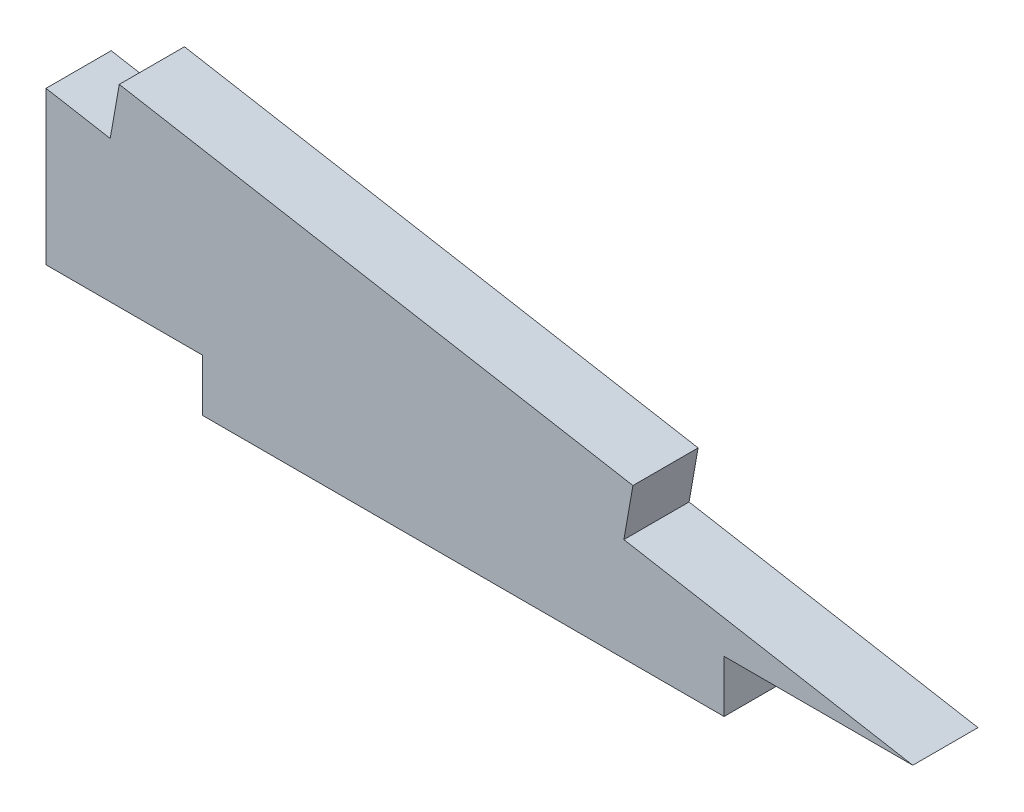
SolidWorks part; units mm, degrees
ref_plane "前视基准面" through (0, 0, 0) normal (0, 0, 1) x (1, 0, 0)
ref_plane "上视基准面" through (0, 0, 0) normal (0, 1, 0) x (1, 0, 0)
ref_plane "右视基准面" through (0, 0, 0) normal (1, 0, 0) x (0, 0, -1)
other "Configuration Table"
sketch "草图1" plane through (0, 0, 0) normal (0, 0, 1) x (1, 0, 0)
  line L2 (-22.4517, 2.9218) -> (-22.4517, 6.9218)
  line L3 (17.5483, 2.9218) -> (17.5483, 6.9218)
  line L4 (-22.4517, 6.9218) -> (-34.4517, 6.9218)
  line L5 (17.5483, 6.9218) -> (24.7855, 6.9218)
  line L6 (-34.4517, 6.9218) -> (-34.4517, 18.6431)
  line L7 (-34.4517, 18.6431) -> (-29.5277, 17.7748)
  line L10 (-29.5277, 17.7748) -> (-28.8331, 21.7141)
  line L11 (-28.8331, 21.7141) -> (10.5592, 14.7681)
  line L12 (10.5592, 14.7681) -> (9.8646, 10.8289)
  line L15 (-22.4517, 2.9218) -> (17.5483, 2.9218)
  line L16 (20.9437, 8.8754) -> (9.8646, 10.8289)
  line L17 (20.9437, 8.8754) -> (32.0228, 6.9218)
  line L18 (24.7855, 6.9218) -> (32.0228, 6.9218)
  point P4 (0, 0)
  dimension "D1" = 40
  dimension "D2" = 4
  dimension "D3" = 12
  dimension "D4" = 4
  dimension "D5" = 40
  dimension "D6" = 4
  dimension "D7" = 4
  dimension "D8" = 22.5
  dimension "D9" = 90
  dimension "D10" = 90
  dimension "D11" = 90
  dimension "D12" = 90
  dimension "D13" = 90
  dimension "D14" = 90
  dimension "D15" = 10
  dimension "D16" = 10
  dimension "D17" = 90
  dimension "D18" = 90
  dimension "D19" = 5
  dimension "D20" = 90
  dimension "D21" = 90
  dimension "D22" = 10
  dimension "D23" = 14.4745
extrude "凸台-拉伸1" add sketch "草图1" along normal blind 5
